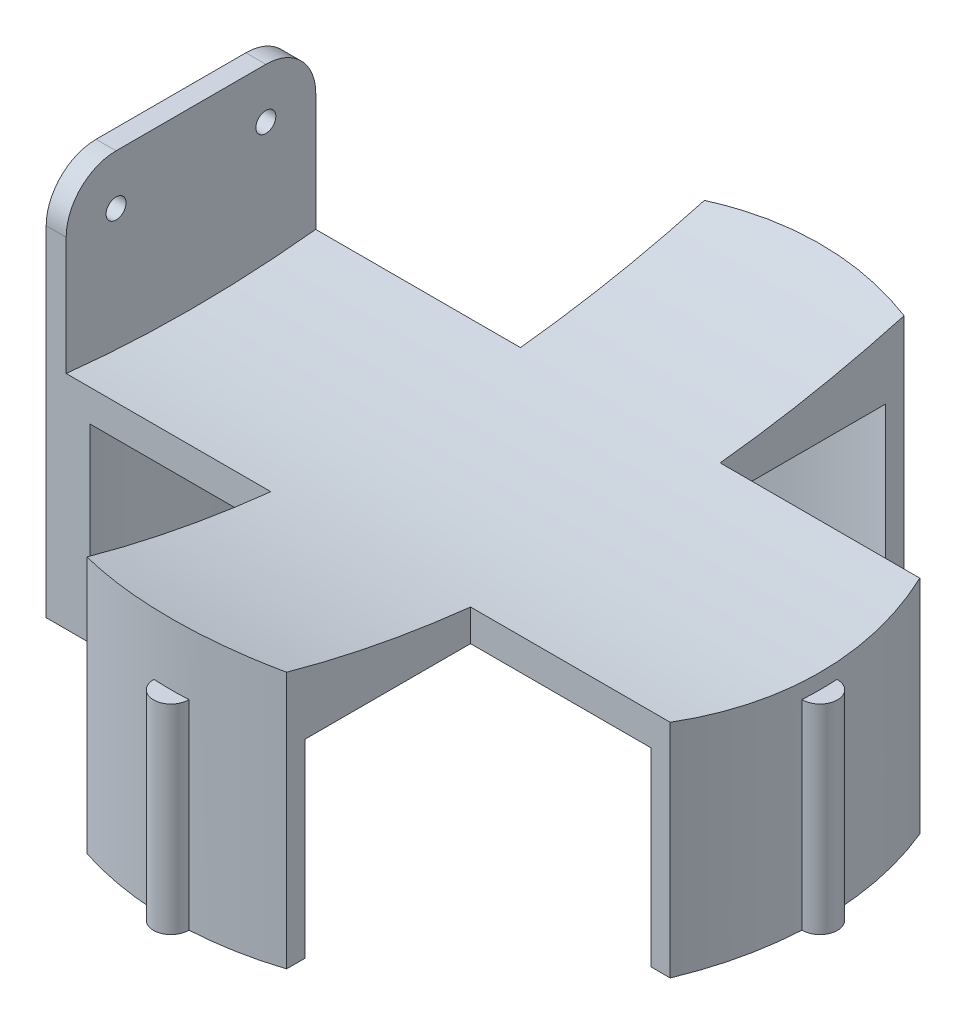
SolidWorks part; units mm, degrees
ref_plane "前视基准面" through (0, 0, 0) normal (0, 0, 1) x (1, 0, 0)
ref_plane "上视基准面" through (0, 0, 0) normal (0, 1, 0) x (1, 0, 0)
ref_plane "右视基准面" through (0, 0, 0) normal (1, 0, 0) x (0, 0, -1)
sketch "草图1" plane through (0, 0, 0) normal (1, 0, 0) x (0, 0, -1)
  line L1 (-25, 0) -> (25, 0)
  line L2 (-25, 0) -> (-25, -40)
  line L3 (-25, -40) -> (25, -40)
  line L4 (25, 0) -> (25, -40)
  dimension "D1" = 50
  dimension "D2" = 25
  dimension "D3" = 40
extrude "凸台-拉伸1" add sketch "草图1" along normal blind 4
sketch "草图2" plane through (4, 0, 0) normal (1, 0, 0) x (0, 0, -1)
  line L1 (-15, -10) -> (15, -10) construction
  line L2 (25, 0) -> (-25, 0) construction
  circle A0 centre (-15, -10) radius 2
  circle A1 centre (15, -10) radius 2
  dimension "D4" = 4
  dimension "D5" = 4
  dimension "D1" = 30
  dimension "D2" = 10
  dimension "D3" = 15
extrude "切除-拉伸1" cut sketch "草图2" against normal blind 4
sketch "草图3" plane through (4, 0, 0) normal (1, 0, 0) x (0, 0, -1)
  line L0 (-25, -40) -> (25, -40) construction
  line L1 (-25, -33.6373) -> (-25, -38.6664)
  line L2 (-25, 0) -> (-25, -40) construction
  line L6 (25, -40) -> (25, 0) construction
  line L7 (25, -38.6664) -> (25, -33.6373)
  arc A0 (-25, -33.6373) -> (25, -33.6373) centre (0, 195) ccw
  arc A1 (-25, -38.6664) -> (25, -38.6664) centre (0, 195) ccw
  dimension "D1" = 460
  dimension "D2" = 470
extrude "凸台-拉伸2" add sketch "草图3" along normal blind 180
sketch "草图4" plane through (4, 0, 0) normal (1, 0, 0) x (0, 0, -1)
  line L2 (0, -40) -> (25, -40)
  line L3 (25, -40) -> (25, -38.6664)
  line L4 (0, -40) -> (25, -40)
  line L5 (25, -40) -> (25, -38.6664)
  line L6 (-25, -38.6664) -> (-25, -40)
  line L7 (-25, -40) -> (0, -40)
  line L8 (-25, -38.6664) -> (-25, -40)
  line L9 (-25, -40) -> (0, -40)
  arc A1 (0, -40) -> (25, -38.6664) centre (0, 195) ccw
  arc A2 (0, -40) -> (25, -38.6664) centre (0, 195) ccw
  arc A3 (-25, -38.6664) -> (0, -40) centre (0, 195) ccw
  arc A4 (-25, -38.6664) -> (0, -40) centre (0, 195) ccw
  arc M7 (25, -38.6664) -> (0, -40) centre (0, 195) cw
  line M8 (0, -40) -> (25, -40)
  line M9 (25, -40) -> (25, -38.6664)
  dimension "D1" = 0
  dimension "D2" = 0
extrude "切除-拉伸2" cut sketch "草图4" against normal blind 60 contours M9 M7 M8
sketch "草图5" plane through (4, 0, 0) normal (1, 0, 0) x (0, 0, -1)
  line L2 (-25, -38.6664) -> (-25, -40)
  line L3 (-25, -40) -> (0, -40)
  line L4 (-25, -38.6664) -> (-25, -40)
  line L5 (-25, -40) -> (0, -40)
  arc A1 (-25, -38.6664) -> (0, -40) centre (0, 195) ccw
  arc A2 (-25, -38.6664) -> (0, -40) centre (0, 195) ccw
  dimension "D1" = 0
extrude "切除-拉伸3" cut sketch "草图5" against normal blind 60
ref_plane "基准面1" through (0, -40, 0) normal (0, -1, 0) x (-1, 0, 0)
sketch "草图6" plane through (0, -40, 0) normal (0, -1, 0) x (-1, 0, 0)
  line L2 (-85.0023, 61.8458) -> (-85.0023, 25)
  line L4 (-45.0023, 61.8473) -> (-45.0023, 25)
  line L5 (-125, 25) -> (-85.0023, 25)
  line L7 (-125, -25) -> (-85.0023, -25)
  line L9 (-85.0023, -25) -> (-85.0023, -61.8458)
  line L10 (-45.0023, -25) -> (-45.0023, -61.8473)
  line L11 (-45.0023, 25) -> (-5, 25)
  line L12 (-45.0023, -25) -> (-5, -25)
  arc A0 (-5, -25) -> (-5, 25) centre (-65, 0) ccw
  arc A1 (-85.0023, -61.8458) -> (-45.0023, -61.8473) centre (-65, 0) ccw
  arc A2 (-125, 25) -> (-125, -25) centre (-65, 0) ccw
  arc A3 (-45.0023, 61.8473) -> (-85.0023, 61.8458) centre (-65, 0) ccw
  dimension "D1" = 130
  dimension "D2" = 50
  dimension "D3" = 40
  dimension "D4" = 25
  dimension "D5" = 65
  dimension "D7" = 45.0023
extrude "凸台-拉伸3" add sketch "草图6" against normal up to surface (6.3627 mm away)
mirror "镜向1" about plane through (0, 0, 0) normal (0, 0, 1) of "凸台-拉伸3"
sketch "草图7" plane through (0, -40, 0) normal (0, -1, 0) x (1, 0, 0)
  line L8 (5, -25) -> (45.0023, -25)
  line L9 (45.0023, -25) -> (45.0023, -61.8473)
  line L10 (85.0023, -61.8458) -> (85.0023, -25)
  line L11 (85.0023, -25) -> (125, -25)
  line L12 (125, 25) -> (85.0023, 25)
  line L13 (85.0023, 25) -> (85.0023, 61.8458)
  line L14 (45.0023, 61.8473) -> (45.0023, 25)
  line L15 (45.0023, 25) -> (5, 25)
  line L16 (5, -25) -> (8.8106, -25)
  line L17 (45.0023, -58.1579) -> (45.0023, -61.8473)
  line L18 (85.0023, -61.8458) -> (85.0023, -58.1563)
  line L19 (121.1894, -25) -> (125, -25)
  line L20 (125, 25) -> (121.1894, 25)
  line L21 (85.0023, 58.1563) -> (85.0023, 61.8458)
  line L22 (45.0023, 61.8473) -> (45.0023, 58.1579)
  line L23 (8.8106, 25) -> (5, 25)
  arc A0 (8.8106, 25) -> (8.8106, -25) centre (65, 0) ccw
  arc A1 (85.0023, 58.1563) -> (45.0023, 58.1579) centre (65, 0) ccw
  arc A2 (121.1894, -25) -> (121.1894, 25) centre (65, 0) ccw
  arc A3 (45.0023, -58.1579) -> (85.0023, -58.1563) centre (65, 0) ccw
  arc A7 (5, 25) -> (0, 0) centre (65, 0) ccw
  arc A8 (0, 0) -> (5, -25) centre (65, 0) ccw
  arc A9 (45.0023, -61.8473) -> (85.0023, -61.8458) centre (65, 0) ccw
  arc A10 (125, -25) -> (130, 0) centre (65, 0) ccw
  arc A11 (130, 0) -> (125, 25) centre (65, 0) ccw
  arc A12 (85.0023, 61.8458) -> (45.0023, 61.8473) centre (65, 0) ccw
  arc A13 (5, 25) -> (0, 0) centre (65, 0) ccw
  arc A14 (0, 0) -> (5, -25) centre (65, 0) ccw
  arc A15 (45.0023, -61.8473) -> (85.0023, -61.8458) centre (65, 0) ccw
  arc A16 (125, -25) -> (130, 0) centre (65, 0) ccw
  arc A17 (130, 0) -> (125, 25) centre (65, 0) ccw
  arc A18 (85.0023, 61.8458) -> (45.0023, 61.8473) centre (65, 0) ccw
  dimension "D1" = 123
  dimension "D2" = 65
  dimension "D3" = 0
extrude "凸台-拉伸4" add sketch "草图7" along normal blind 38
sketch "草图8" plane through (0, -78, 0) normal (0, -1, 0) x (1, 0, 0)
  line L3 (184, 25) -> (125, 25)
  line L4 (125, -25) -> (184, -25)
  line L5 (184, -25) -> (184, 25)
  line L6 (184, 25) -> (125, 25)
  line L7 (125, -25) -> (184, -25)
  line L8 (184, -25) -> (184, 25)
  arc A1 (125, -25) -> (125, 25) centre (65, 0) ccw
  arc A2 (125, -25) -> (125, 25) centre (65, 0) ccw
  dimension "D1" = 0
extrude "切除-拉伸4" cut sketch "草图8" against normal through all
sketch "草图9" plane through (0, -78, 0) normal (0, -1, 0) x (1, 0, 0)
  circle A0 centre (130, 0) radius 3.5
  arc A1 (125, -25) -> (125, 25) centre (65, 0) ccw construction
  circle A2 centre (65.0025, -65) radius 3.5
  arc A3 (45.0023, -61.8473) -> (85.0023, -61.8458) centre (65, 0) ccw construction
  circle A4 centre (65.0025, 65) radius 3.5
  arc A5 (85.0023, 61.8458) -> (45.0023, 61.8473) centre (65, 0) ccw construction
  dimension "D1" = 7
  dimension "D2" = 7
  dimension "D3" = 7
extrude "凸台-拉伸5" add sketch "草图9" against normal blind 40
sketch "草图10" plane through (0, -78, 0) normal (0, -1, 0) x (1, 0, 0)
  circle A0 centre (65.0025, 65) radius 1.5
  circle A1 centre (130, 0) radius 1.5
  circle A2 centre (65.0025, -65) radius 1.5
  dimension "D1" = 3
  dimension "D2" = 3
  dimension "D3" = 3
extrude "切除-拉伸5" cut sketch "草图10" against normal blind 30
chamfer "倒角1" distance 0.5 angle 45 3 edges at (65.0025, -78, 63.5) (130, -78, -1.5) (65.0025, -78, -66.5)
sketch "草图11" plane through (0, -78, 0) normal (0, -1, 0) x (1, 0, 0)
  line L2 (0, 25) -> (0, 0)
  line L3 (5, 25) -> (0, 25)
  line L4 (0, 25) -> (0, 0)
  line L5 (5, 25) -> (0, 25)
  arc A1 (5, 25) -> (0, 0) centre (65, 0) ccw
  arc A2 (5, 25) -> (0, 0) centre (65, 0) ccw
  dimension "D1" = 0
extrude "凸台-拉伸6" add sketch "草图11" against normal up to next
sketch "草图12" plane through (0, -78, 0) normal (0, -1, 0) x (1, 0, 0)
  line L2 (0, -25) -> (5, -25)
  line L3 (0, 0) -> (0, -25)
  line L4 (0, -25) -> (5, -25)
  line L5 (0, 0) -> (0, -25)
  arc A1 (0, 0) -> (5, -25) centre (65, 0) ccw
  arc A2 (0, 0) -> (5, -25) centre (65, 0) ccw
  dimension "D1" = 0
extrude "凸台-拉伸7" add sketch "草图12" against normal up to next
fillet "圆角1" radius 10 2 edges at (2, 0, 25) (2, 0, -25)
